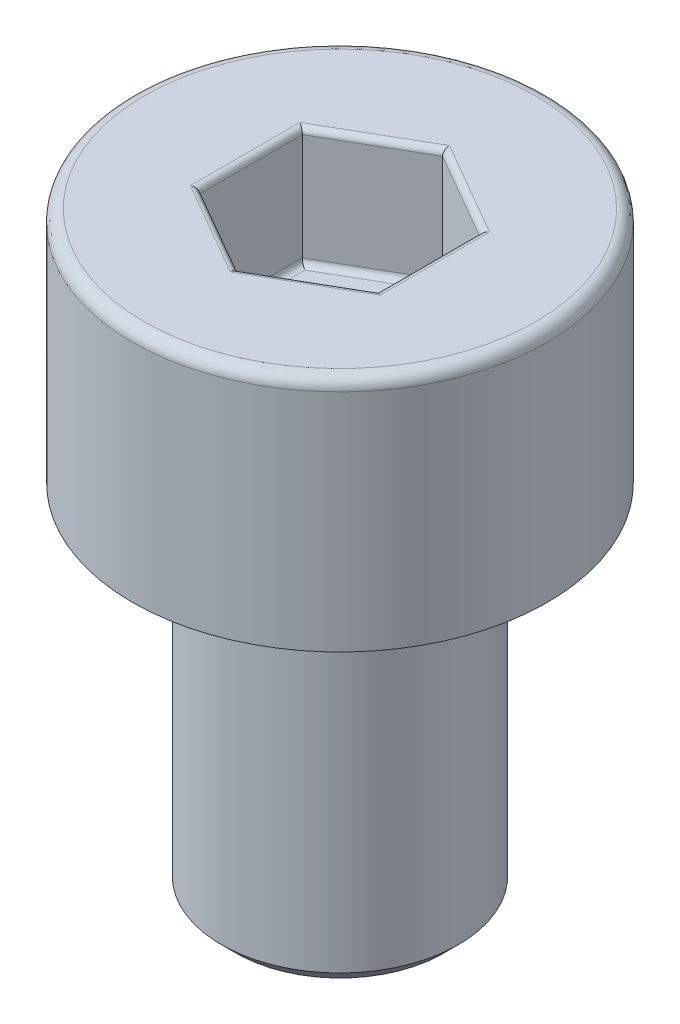
SolidWorks part; units mm, degrees
ref_plane "Front Plane" through (0, 0, 0) normal (0, 0, 1) x (1, 0, 0)
ref_plane "Top Plane" through (0, 0, 0) normal (0, 1, 0) x (1, 0, 0)
ref_plane "Right Plane" through (0, 0, 0) normal (1, 0, 0) x (0, 0, -1)
sketch "Sketch1" plane through (0, 0, 0) normal (0, 0, 1) x (1, 0, 0)
  line L0 (0, 0) -> (0, -47.0967) construction
  line L1 (0, -10) -> (-2, -10)
  line L2 (-2, -10) -> (-2, -4)
  line L3 (-2, -4) -> (-3.5, -4)
  line L4 (-3.5, -4) -> (-3.5, 0)
  line L5 (-3.5, 0) -> (0, 0)
  line L6 (0, 0) -> (0, -10)
  dimension "D1" = 6
  dimension "d" = 4
  dimension "k" = 4
  dimension "dk" = 7
revolve "Revolve1" add sketch "Sketch1" angle 360 about L0
chamfer "Chamfer1" distance 0.25 angle 45 2 edges at (0, -4, 2) (0, -10, 2)
fillet "Fillet1" radius 0.2 1 edges at (0, 0, 3.5)
sketch "Sketch2" plane through (0, 0, 0) normal (0, 1, 0) x (1, 0, 0)
  line L1 (0, 1.7321) -> (-1.5, 0.866)
  line L2 (-1.5, 0.866) -> (-1.5, -0.866)
  line L3 (-1.5, -0.866) -> (0, -1.7321)
  line L4 (0, -1.7321) -> (1.5, -0.866)
  line L5 (1.5, -0.866) -> (1.5, 0.866)
  line L6 (1.5, 0.866) -> (0, 1.7321)
  circle A0 centre (0, 0) radius 1.5 construction
  dimension "s" = 3
extrude "Cut-Extrude1" cut sketch "Sketch2" against normal blind 2
fillet "Fillet2" radius 0.1 12 edges at (-0.75, 0, -1.299) (-1.5, 0, 0) (-0.75, 0, 1.299) (0.75, 0, 1.299) (1.5, 0, 0) (0.75, 0, -1.299) (1.5, -2, 0) (0.75, -2, 1.299) (-0.75, -2, 1.299) (-1.5, -2, 0) (-0.75, -2, -1.299) (0.75, -2, -1.299)
